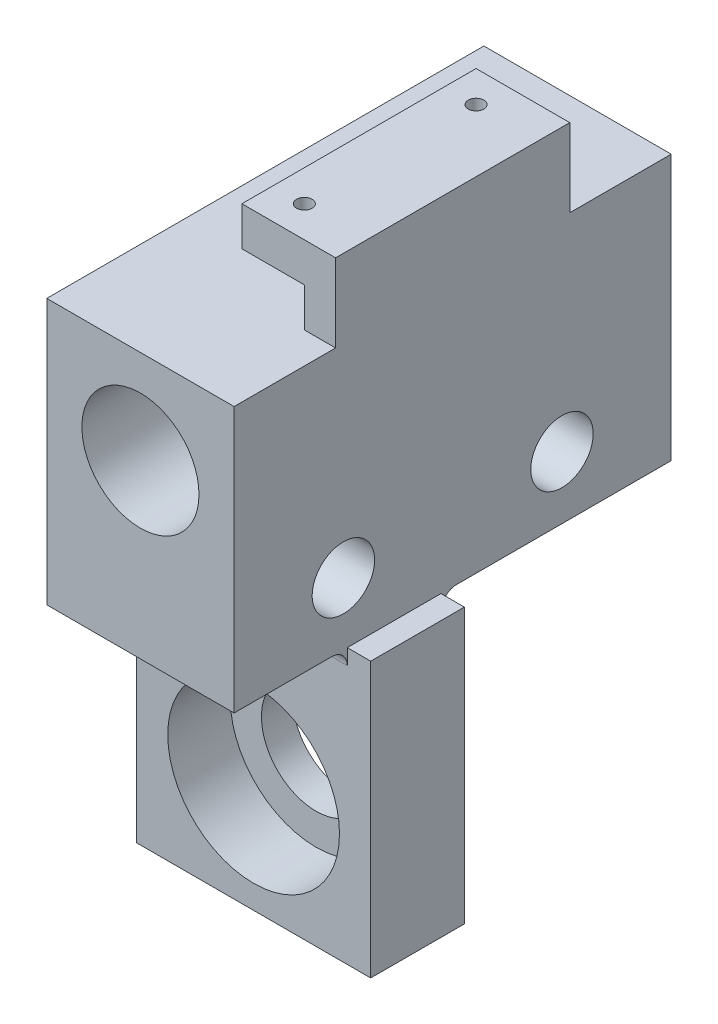
SolidWorks part; units mm, degrees
ref_plane "Front Plane" through (0, 0, 0) normal (0, 0, 1) x (1, 0, 0)
ref_plane "Top Plane" through (0, 0, 0) normal (0, 1, 0) x (1, 0, 0)
ref_plane "Right Plane" through (0, 0, 0) normal (1, 0, 0) x (0, 0, -1)
sketch "Sketch1" plane through (0, 0, 0) normal (0, 0, 1) x (1, 0, 0)
  line L1 (-12, 12) -> (12, 12)
  line L2 (-12, 12) -> (-12, -22)
  line L3 (-12, -22) -> (12, -22)
  line L4 (12, 12) -> (12, -22)
  circle A0 centre (0, 0) radius 7.5
  dimension "D1" = 12
  dimension "D5" = 15
  dimension "D2" = 24
  dimension "D3" = 12
  dimension "D4" = 34
extrude "Boss-Extrude1" add sketch "Sketch1" along normal mid plane 56
sketch "Sketch3" plane through (0, -22, 0) normal (0, -1, 0) x (1, 0, 0)
  line L1 (-15, 13.5) -> (15, 13.5)
  line L2 (-15, 13.5) -> (-15, 1.5)
  line L3 (-15, 1.5) -> (15, 1.5)
  line L4 (15, 13.5) -> (15, 1.5)
  dimension "D1" = 30
  dimension "D2" = 15
  dimension "D3" = 13.5
  dimension "D4" = 12
extrude "Boss-Extrude2" add sketch "Sketch3" along normal blind 35.15
sketch "Sketch4" plane through (0, 0, 13.5) normal (0, 0, 1) x (1, 0, 0)
  line L0 (15, -57.15) -> (-15, -57.15) construction
  line L1 (15, -57.15) -> (15, -22) construction
  circle A0 centre (0, -43.15) radius 11
  dimension "D1" = 22
  dimension "D2" = 14
  dimension "D3" = 15
extrude "Cut-Extrude2" cut sketch "Sketch4" against normal blind 8
fillet "Fillet1" radius 2 2 edges at (0, -22, 1.5) (0, -22, 13.5)
sketch "Sketch5" plane through (0, 12, 0) normal (0, 1, 0) x (1, 0, 0)
  line L0 (12, -28) -> (12, 28) construction
  line L1 (0, 15) -> (12, 15)
  line L2 (0, 15) -> (0, -15)
  line L3 (0, -15) -> (12, -15)
  line L4 (12, 15) -> (12, -15)
  point P6 (12, 0)
  dimension "D1" = 30
  dimension "D2" = 12
extrude "Boss-Extrude3" add sketch "Sketch5" along normal blind 10
sketch "Sketch6" plane through (0, 0, 15) normal (0, 0, 1) x (1, 0, 0)
  line L0 (0, 22) -> (0, 12) construction
  line L1 (0, 17) -> (8, 17)
  line L2 (0, 17) -> (0, 12)
  line L3 (0, 12) -> (8, 12)
  line L4 (8, 17) -> (8, 12)
  line L5 (0, 12) -> (12, 12) construction
  dimension "D1" = 8
  dimension "D2" = 5
extrude "Cut-Extrude3" cut sketch "Sketch6" against normal through all
sketch "Sketch7" plane through (0, 22, 0) normal (0, 1, 0) x (1, 0, 0)
  line L0 (0, -15) -> (12, -15) construction
  line L1 (0, 15) -> (0, -15) construction
  line L3 (12, 15) -> (0, 15) construction
  circle A0 centre (4, 11) radius 1
  circle A1 centre (4, -11) radius 1
  dimension "D1" = 2
  dimension "D2" = 4
  dimension "D3" = 4
  dimension "D4" = 4
  dimension "D5" = 4
extrude "Cut-Extrude4" cut sketch "Sketch7" against normal up to next
sketch "Sketch8" plane through (12, 0, 0) normal (1, 0, 0) x (0, 0, -1)
  line L2 (-28, -22) -> (-15.5, -22) construction
  circle A0 centre (-14, -14) radius 4
  circle A1 centre (14, -14) radius 4
  dimension "D1" = 8
  dimension "D2" = 28
  dimension "D4" = 8
  dimension "D5" = 14
extrude "Cut-Extrude5" cut sketch "Sketch8" against normal blind 20
sketch "Sketch9" plane through (0, 0, 5.5) normal (0, 0, 1) x (1, 0, 0)
  circle A0 centre (0, -43.15) radius 7
  circle A1 centre (0, -43.15) radius 11 construction
  dimension "D1" = 14
extrude "Cut-Extrude6" cut sketch "Sketch9" against normal blind 10
